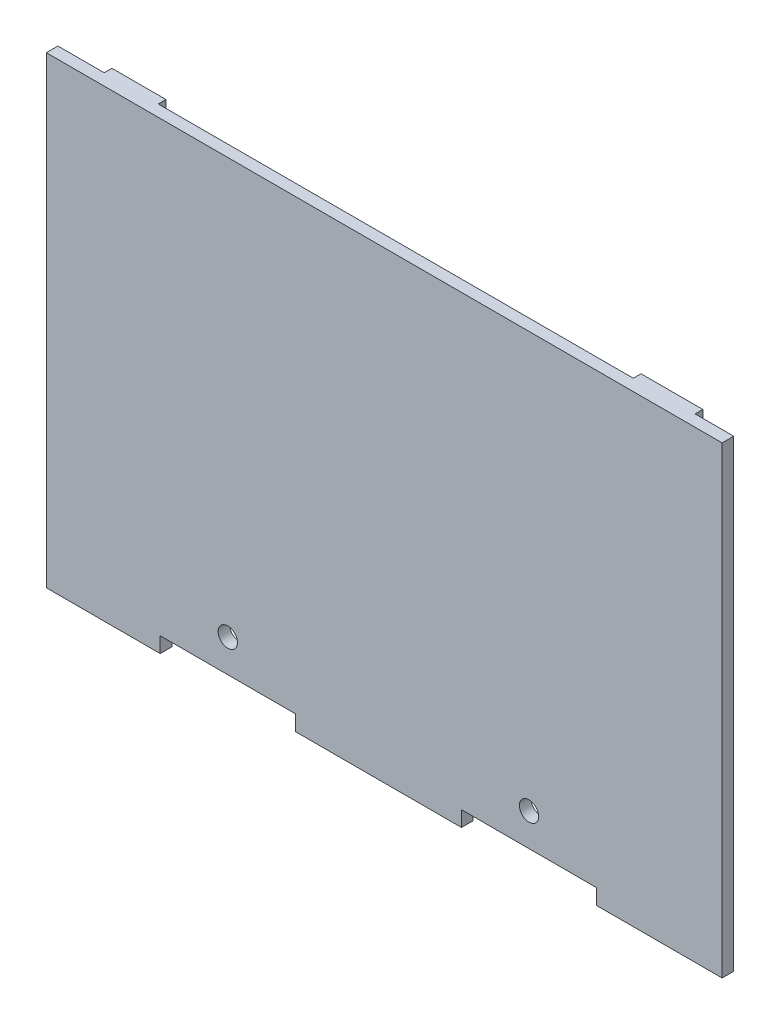
SolidWorks part; units mm, degrees
ref_plane "Front Plane" through (0, 0, 0) normal (0, 0, 1) x (1, 0, 0)
ref_plane "Top Plane" through (0, 0, 0) normal (0, 1, 0) x (1, 0, 0)
ref_plane "Right Plane" through (0, 0, 0) normal (1, 0, 0) x (0, 0, -1)
sketch "Esquisse2" plane through (0, 0, 0) normal (0, 0, 1) x (1, 0, 0)
  line L0 (0, 0) -> (175, 0)
  line L1 (175, 0) -> (175, -120)
  line L2 (175, -120) -> (142.5, -120)
  line L3 (142.5, -120) -> (142.5, -116)
  line L4 (142.5, -116) -> (107.5, -116)
  line L5 (107.5, -116) -> (107.5, -120)
  line L6 (107.5, -120) -> (64.5, -120)
  line L7 (64.5, -120) -> (64.5, -116)
  line L8 (64.5, -116) -> (29.5, -116)
  line L9 (29.5, -116) -> (29.5, -120)
  line L10 (29.5, -120) -> (0, -120)
  line L11 (0, -120) -> (0, 0)
  line L12 (87.5, 0) -> (87.5, -120) construction
  point P3 (86, -120)
  point P14 (87.5, -120)
  dimension "D1" = 35
  dimension "D2" = 35
  dimension "D3" = 20
  dimension "D4" = 175
  dimension "D5" = 23
  dimension "D6" = 120
  dimension "D7" = 4
  dimension "D8" = 4
extrude "Boss.-Extru.1" add sketch "Esquisse2" along normal blind 3
sketch "Esquisse3" plane through (0, 0, 3) normal (0, 0, 1) x (1, 0, 0)
  line L0 (175, 0) -> (0, 0) construction
  line L1 (12, 0) -> (26, 0)
  line L2 (12, 0) -> (12, -120)
  line L3 (12, -120) -> (26, -120)
  line L4 (26, 0) -> (26, -120)
  line L5 (0, -120) -> (29.5, -120) construction
  line L6 (142.5, -120) -> (175, -120) construction
  line L7 (149, 0) -> (165, 0)
  line L8 (149, 0) -> (149, -120)
  line L9 (149, -120) -> (165, -120)
  line L10 (165, 0) -> (165, -120)
  line L11 (87.5, 0) -> (87.5, -120) construction
  line L12 (64.5, -120) -> (107.5, -120) construction
  line L13 (26, 0) -> (87.5, 0) construction
  line L14 (87.5, 0) -> (149, 0) construction
  line L15 (0, 0) -> (0, -120) construction
  point P18 (19, 0)
  dimension "D1" = 14
  dimension "D2" = 16
  dimension "D3" = 19
extrude "Boss.-Extru.2" add sketch "Esquisse3" against normal blind 5
sketch "Esquisse4" plane through (0, 0, 3) normal (0, 0, 1) x (1, 0, 0)
  line L0 (29.5, -116) -> (64.5, -116) construction
  line L1 (107.5, -116) -> (142.5, -116) construction
  line L2 (29.5, -116) -> (64.5, -116) construction
  line L3 (107.5, -116) -> (142.5, -116) construction
  circle A0 centre (47, -107.55) radius 2.5
  circle A1 centre (125, -107.55) radius 2.5
  point P10 (47, -116)
  point P13 (125, -116)
  dimension "D1" = 5
  dimension "D2" = 5
  dimension "D3" = 8.45
  dimension "D4" = 8.45
extrude "Enlèv. mat.-Extru.1" cut sketch "Esquisse4" against normal blind 10
